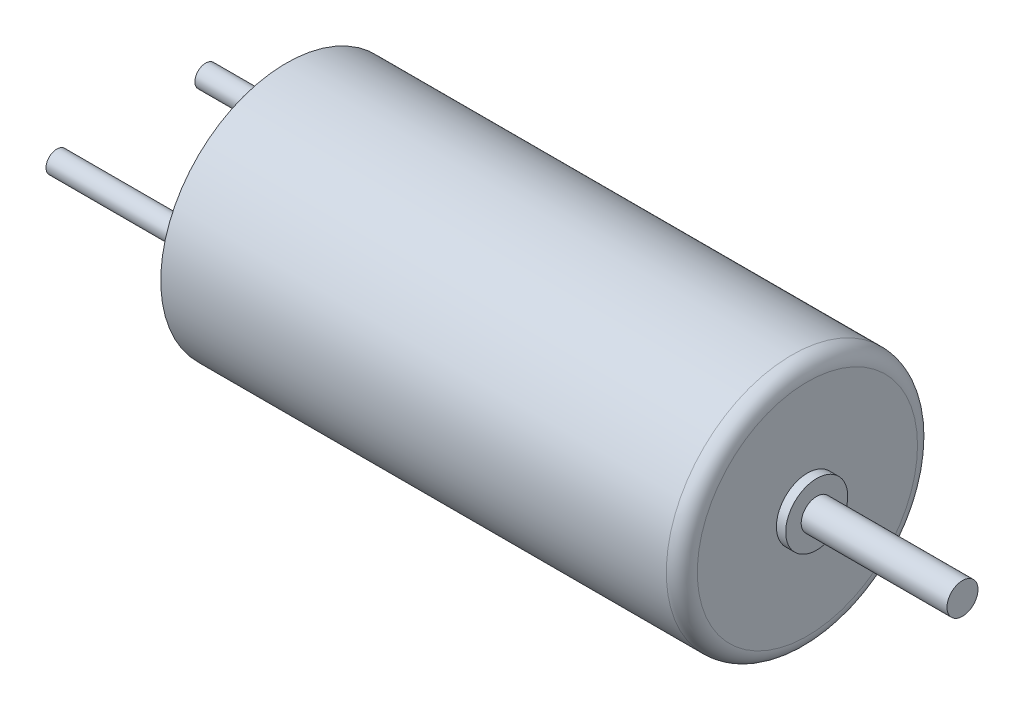
SolidWorks part; units mm, degrees
ref_plane "Front Plane" through (0, 0, 0) normal (0, 0, 1) x (1, 0, 0)
ref_plane "Top Plane" through (0, 0, 0) normal (0, 1, 0) x (1, 0, 0)
ref_plane "Right Plane" through (0, 0, 0) normal (1, 0, 0) x (0, 0, -1)
sketch "Sketch1" plane through (0, 0, 0) normal (1, 0, 0) x (0, 0, -1)
  circle A0 centre (0, 0) radius 4.05
  dimension "D1" = 8.1
extrude "Boss-Extrude1" add sketch "Sketch1" along normal blind 16.8 contours A0
sketch "Sketch2" plane through (16.8, 0, 0) normal (1, 0, 0) x (0, 0, -1)
  circle A0 centre (0, 0) radius 1
  dimension "D1" = 2
extrude "Boss-Extrude2" add sketch "Sketch2" along normal blind 0.3
sketch "Sketch3" plane through (17.1, 0, 0) normal (1, 0, 0) x (0, 0, -1)
  circle A0 centre (0, 0) radius 0.5
  dimension "D1" = 1
extrude "Boss-Extrude3" add sketch "Sketch3" along normal blind 4.7 contours A0
sketch "Sketch4" plane through (0, 0, 0) normal (-1, 0, 0) x (0, 0, 1)
  circle A0 centre (0, 0) radius 2.4 construction
  circle A1 centre (2.4, 0) radius 0.35
  circle A2 centre (-2.4, 0) radius 0.35
  dimension "D1" = 4.8
  dimension "D2" = 0.7
extrude "Boss-Extrude4" add sketch "Sketch4" along normal blind 5
fillet "Fillet1" radius 0.5 1 edges at (16.8, 0, -4.05)
